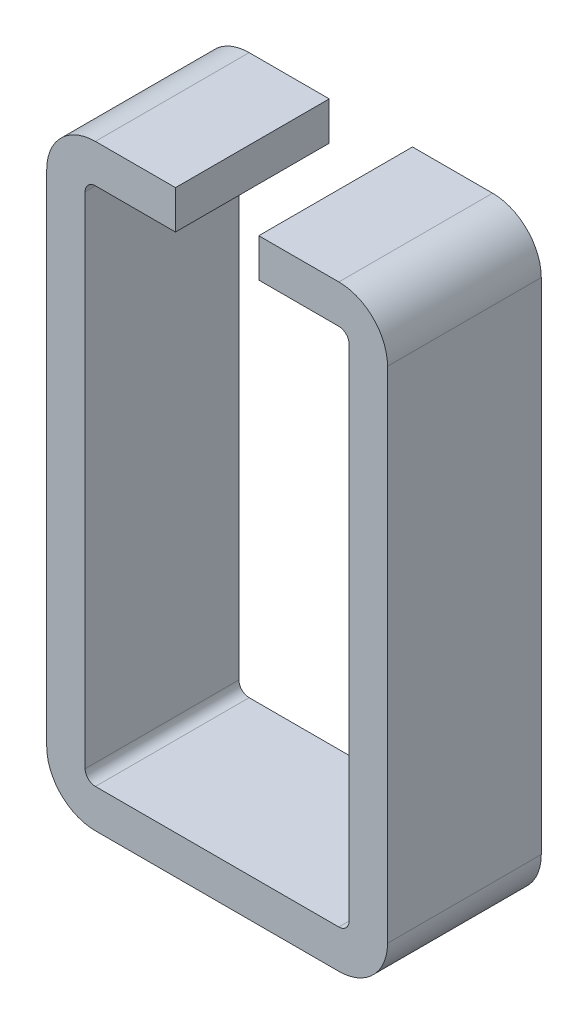
SolidWorks part; units mm, degrees
ref_plane "Front Plane" through (0, 0, 0) normal (0, 0, 1) x (1, 0, 0)
ref_plane "Top Plane" through (0, 0, 0) normal (0, 1, 0) x (1, 0, 0)
ref_plane "Right Plane" through (0, 0, 0) normal (1, 0, 0) x (0, 0, -1)
sketch "Sketch1" plane through (0, 0, 0) normal (0, 0, 1) x (1, 0, 0)
  line L0 (-3.25, 20.3) -> (-3.25, 23.3)
  line L1 (-3.05, 20.9) -> (-3.05, 23.3537) construction
  line L2 (3.25, 23.3) -> (3.25, 20.3)
  line L3 (3.05, 20.9) -> (3.05, 23.3537) construction
  line L94 (-10, -14.58) -> (-10, -19.5)
  line L95 (-9.5, -20) -> (-4.58, -20)
  line L96 (-4.58, -20) -> (-3.125, -18.545)
  line L97 (-3.125, -18.545) -> (-3.125, -18.2)
  line L98 (-3.125, -18.2) -> (-5.5, -18.2)
  line L99 (-5.5, -18.2) -> (-5.5, -16.5607)
  line L100 (-5.5, -16.5607) -> (-2.8393, -13.9)
  line L101 (-2.8393, -13.9) -> (-0.2, -13.9)
  line L102 (-0.2, -13.9) -> (0, -13.7)
  line L103 (0, -13.7) -> (0.2, -13.9)
  line L104 (0.2, -13.9) -> (2.8393, -13.9)
  line L105 (2.8393, -13.9) -> (5.5, -16.5607)
  line L106 (5.5, -16.5607) -> (5.5, -18.2)
  line L107 (5.5, -18.2) -> (3.125, -18.2)
  line L108 (3.125, -18.2) -> (3.125, -18.545)
  line L109 (3.125, -18.545) -> (4.58, -20)
  line L110 (4.58, -20) -> (9.5, -20)
  line L111 (10, -19.5) -> (10, -14.58)
  line L112 (10, -14.58) -> (8.545, -13.125)
  line L113 (8.545, -13.125) -> (8.2, -13.125)
  line L114 (8.2, -13.125) -> (8.2, -15.5)
  line L115 (8.2, -15.5) -> (6.5607, -15.5)
  line L116 (6.5607, -15.5) -> (3.9, -12.8393)
  line L117 (3.9, -12.8393) -> (3.9, -10.2)
  line L118 (3.9, -10.2) -> (3.7, -10)
  line L119 (3.7, -10) -> (3.9, -9.8)
  line L120 (3.9, -9.8) -> (3.9, -7.1607)
  line L121 (3.9, -7.1607) -> (6.5607, -4.5)
  line L122 (6.5607, -4.5) -> (8.2, -4.5)
  line L123 (8.2, -4.5) -> (8.2, -6.875)
  line L124 (8.2, -6.875) -> (8.545, -6.875)
  line L125 (8.545, -6.875) -> (10, -5.42)
  line L126 (10, -5.42) -> (10, 5.42)
  line L127 (10, 5.42) -> (8.545, 6.875)
  line L128 (8.545, 6.875) -> (8.2, 6.875)
  line L129 (8.2, 6.875) -> (8.2, 4.5)
  line L130 (8.2, 4.5) -> (6.5607, 4.5)
  line L131 (6.5607, 4.5) -> (3.9, 7.1607)
  line L132 (3.9, 7.1607) -> (3.9, 9.8)
  line L133 (3.9, 9.8) -> (3.7, 10)
  line L134 (3.7, 10) -> (3.9, 10.2)
  line L135 (3.9, 10.2) -> (3.9, 12.8393)
  line L136 (3.9, 12.8393) -> (6.5607, 15.5)
  line L137 (6.5607, 15.5) -> (8.2, 15.5)
  line L138 (8.2, 15.5) -> (8.2, 13.125)
  line L139 (8.2, 13.125) -> (8.545, 13.125)
  line L140 (8.545, 13.125) -> (10, 14.58)
  line L141 (10, 14.58) -> (10, 19.5)
  line L142 (9.5, 20) -> (4.58, 20)
  line L143 (4.58, 20) -> (3.125, 18.545)
  line L144 (3.125, 18.545) -> (3.125, 18.2)
  line L145 (3.125, 18.2) -> (5.5, 18.2)
  line L146 (5.5, 18.2) -> (5.5, 16.5607)
  line L147 (5.5, 16.5607) -> (2.8393, 13.9)
  line L148 (2.8393, 13.9) -> (0.2, 13.9)
  line L149 (0.2, 13.9) -> (0, 13.7)
  line L150 (0, 13.7) -> (-0.2, 13.9)
  line L151 (-0.2, 13.9) -> (-2.8393, 13.9)
  line L152 (-2.8393, 13.9) -> (-5.5, 16.5607)
  line L153 (-5.5, 16.5607) -> (-5.5, 18.2)
  line L154 (-5.5, 18.2) -> (-3.125, 18.2)
  line L155 (-3.125, 18.2) -> (-3.125, 18.545)
  line L156 (-3.125, 18.545) -> (-4.58, 20)
  line L157 (-4.58, 20) -> (-9.5, 20)
  line L158 (-10, 19.5) -> (-10, 14.58)
  line L159 (-10, 14.58) -> (-8.545, 13.125)
  line L160 (-8.545, 13.125) -> (-8.2, 13.125)
  line L161 (-8.2, 13.125) -> (-8.2, 15.5)
  line L162 (-8.2, 15.5) -> (-6.5607, 15.5)
  line L163 (-6.5607, 15.5) -> (-3.9, 12.8393)
  line L164 (-3.9, 12.8393) -> (-3.9, 10.2)
  line L165 (-3.9, 10.2) -> (-3.7, 10)
  line L166 (-3.7, 10) -> (-3.9, 9.8)
  line L167 (-3.9, 9.8) -> (-3.9, 7.1607)
  line L168 (-3.9, 7.1607) -> (-6.5607, 4.5)
  line L169 (-6.5607, 4.5) -> (-8.2, 4.5)
  line L170 (-8.2, 4.5) -> (-8.2, 6.875)
  line L171 (-8.2, 6.875) -> (-8.545, 6.875)
  line L172 (-8.545, 6.875) -> (-10, 5.42)
  line L173 (-10, 5.42) -> (-10, -5.42)
  line L174 (-10, -5.42) -> (-8.545, -6.875)
  line L175 (-8.545, -6.875) -> (-8.2, -6.875)
  line L176 (-8.2, -6.875) -> (-8.2, -4.5)
  line L177 (-8.2, -4.5) -> (-6.5607, -4.5)
  line L178 (-6.5607, -4.5) -> (-3.9, -7.1607)
  line L179 (-3.9, -7.1607) -> (-3.9, -9.8)
  line L180 (-3.9, -9.8) -> (-3.7, -10)
  line L181 (-3.7, -10) -> (-3.9, -10.2)
  line L182 (-3.9, -10.2) -> (-3.9, -12.8393)
  line L183 (-3.9, -12.8393) -> (-6.5607, -15.5)
  line L184 (-6.5607, -15.5) -> (-8.2, -15.5)
  line L185 (-8.2, -15.5) -> (-8.2, -13.125)
  line L186 (-8.2, -13.125) -> (-8.545, -13.125)
  line L187 (-8.545, -13.125) -> (-10, -14.58)
  line L188 (-10, -14.58) -> (-10, -19.5) construction
  line L189 (-9.5, -20) -> (-4.58, -20) construction
  line L190 (-4.58, -20) -> (-3.125, -18.545) construction
  line L191 (-3.125, -18.545) -> (-3.125, -18.2) construction
  line L192 (-3.125, -18.2) -> (-5.5, -18.2) construction
  line L193 (-5.5, -18.2) -> (-5.5, -16.5607) construction
  line L194 (-5.5, -16.5607) -> (-2.8393, -13.9) construction
  line L195 (-2.8393, -13.9) -> (-0.2, -13.9) construction
  line L196 (-0.2, -13.9) -> (0, -13.7) construction
  line L197 (0, -13.7) -> (0.2, -13.9) construction
  line L198 (0.2, -13.9) -> (2.8393, -13.9) construction
  line L199 (2.8393, -13.9) -> (5.5, -16.5607) construction
  line L200 (5.5, -16.5607) -> (5.5, -18.2) construction
  line L201 (5.5, -18.2) -> (3.125, -18.2) construction
  line L202 (3.125, -18.2) -> (3.125, -18.545) construction
  line L203 (3.125, -18.545) -> (4.58, -20) construction
  line L204 (4.58, -20) -> (9.5, -20) construction
  line L205 (10, -19.5) -> (10, -14.58) construction
  line L206 (10, -14.58) -> (8.545, -13.125) construction
  line L207 (8.545, -13.125) -> (8.2, -13.125) construction
  line L208 (8.2, -13.125) -> (8.2, -15.5) construction
  line L209 (8.2, -15.5) -> (6.5607, -15.5) construction
  line L210 (6.5607, -15.5) -> (3.9, -12.8393) construction
  line L211 (3.9, -12.8393) -> (3.9, -10.2) construction
  line L212 (3.9, -10.2) -> (3.7, -10) construction
  line L213 (3.7, -10) -> (3.9, -9.8) construction
  line L214 (3.9, -9.8) -> (3.9, -7.1607) construction
  line L215 (3.9, -7.1607) -> (6.5607, -4.5) construction
  line L216 (6.5607, -4.5) -> (8.2, -4.5) construction
  line L217 (8.2, -4.5) -> (8.2, -6.875) construction
  line L218 (8.2, -6.875) -> (8.545, -6.875) construction
  line L219 (8.545, -6.875) -> (10, -5.42) construction
  line L220 (10, -5.42) -> (10, 5.42) construction
  line L221 (10, 5.42) -> (8.545, 6.875) construction
  line L222 (8.545, 6.875) -> (8.2, 6.875) construction
  line L223 (8.2, 6.875) -> (8.2, 4.5) construction
  line L224 (8.2, 4.5) -> (6.5607, 4.5) construction
  line L225 (6.5607, 4.5) -> (3.9, 7.1607) construction
  line L226 (3.9, 7.1607) -> (3.9, 9.8) construction
  line L227 (3.9, 9.8) -> (3.7, 10) construction
  line L228 (3.7, 10) -> (3.9, 10.2) construction
  line L229 (3.9, 10.2) -> (3.9, 12.8393) construction
  line L230 (3.9, 12.8393) -> (6.5607, 15.5) construction
  line L231 (6.5607, 15.5) -> (8.2, 15.5) construction
  line L232 (8.2, 15.5) -> (8.2, 13.125) construction
  line L233 (8.2, 13.125) -> (8.545, 13.125) construction
  line L234 (8.545, 13.125) -> (10, 14.58) construction
  line L235 (10, 14.58) -> (10, 19.5) construction
  line L236 (9.5, 20) -> (4.58, 20) construction
  line L237 (4.58, 20) -> (3.125, 18.545) construction
  line L238 (3.125, 18.545) -> (3.125, 18.2) construction
  line L239 (3.125, 18.2) -> (5.5, 18.2) construction
  line L240 (5.5, 18.2) -> (5.5, 16.5607) construction
  line L241 (5.5, 16.5607) -> (2.8393, 13.9) construction
  line L242 (2.8393, 13.9) -> (0.2, 13.9) construction
  line L243 (0.2, 13.9) -> (0, 13.7) construction
  line L244 (0, 13.7) -> (-0.2, 13.9) construction
  line L245 (-0.2, 13.9) -> (-2.8393, 13.9) construction
  line L246 (-2.8393, 13.9) -> (-5.5, 16.5607) construction
  line L247 (-5.5, 16.5607) -> (-5.5, 18.2) construction
  line L248 (-5.5, 18.2) -> (-3.125, 18.2) construction
  line L249 (-3.125, 18.2) -> (-3.125, 18.545) construction
  line L250 (-3.125, 18.545) -> (-4.58, 20) construction
  line L251 (-4.58, 20) -> (-9.5, 20) construction
  line L252 (-10, 19.5) -> (-10, 14.58) construction
  line L253 (-10, 14.58) -> (-8.545, 13.125) construction
  line L254 (-8.545, 13.125) -> (-8.2, 13.125) construction
  line L255 (-8.2, 13.125) -> (-8.2, 15.5) construction
  line L256 (-8.2, 15.5) -> (-6.5607, 15.5) construction
  line L257 (-6.5607, 15.5) -> (-3.9, 12.8393) construction
  line L258 (-3.9, 12.8393) -> (-3.9, 10.2) construction
  line L259 (-3.9, 10.2) -> (-3.7, 10) construction
  line L260 (-3.7, 10) -> (-3.9, 9.8) construction
  line L261 (-3.9, 9.8) -> (-3.9, 7.1607) construction
  line L262 (-3.9, 7.1607) -> (-6.5607, 4.5) construction
  line L263 (-6.5607, 4.5) -> (-8.2, 4.5) construction
  line L264 (-8.2, 4.5) -> (-8.2, 6.875) construction
  line L265 (-8.2, 6.875) -> (-8.545, 6.875) construction
  line L266 (-8.545, 6.875) -> (-10, 5.42) construction
  line L267 (-10, 5.42) -> (-10, -5.42) construction
  line L268 (-10, -5.42) -> (-8.545, -6.875) construction
  line L269 (-8.545, -6.875) -> (-8.2, -6.875) construction
  line L270 (-8.2, -6.875) -> (-8.2, -4.5) construction
  line L271 (-8.2, -4.5) -> (-6.5607, -4.5) construction
  line L272 (-6.5607, -4.5) -> (-3.9, -7.1607) construction
  line L273 (-3.9, -7.1607) -> (-3.9, -9.8) construction
  line L274 (-3.9, -9.8) -> (-3.7, -10) construction
  line L275 (-3.7, -10) -> (-3.9, -10.2) construction
  line L276 (-3.9, -10.2) -> (-3.9, -12.8393) construction
  line L277 (-3.9, -12.8393) -> (-6.5607, -15.5) construction
  line L278 (-6.5607, -15.5) -> (-8.2, -15.5) construction
  line L279 (-8.2, -15.5) -> (-8.2, -13.125) construction
  line L280 (-8.2, -13.125) -> (-8.545, -13.125) construction
  line L281 (-8.545, -13.125) -> (-10, -14.58) construction
  line L282 (-10.3, 14.4557) -> (-10.3, 5.5443)
  line L283 (10.3, 14.4557) -> (10.3, 5.5443)
  line L284 (10.3, -5.5443) -> (10.3, -14.4557)
  line L285 (-10.3, -5.5443) -> (-10.3, -14.4557)
  line L286 (-4.4557, -20.3) -> (4.4557, -20.3)
  line L287 (-4.4557, 20.3) -> (4.4557, 20.3)
  line L288 (-4.4557, 23.3) -> (-9.5, 23.3)
  line L289 (-13.3, 19.5) -> (-13.3, 14.4557)
  line L290 (-13.3, 14.4557) -> (-13.3, 5.5443)
  line L291 (-13.3, 5.5443) -> (-13.3, -5.5443)
  line L292 (-13.3, -5.5443) -> (-13.3, -14.4557)
  line L293 (-13.3, -14.4557) -> (-13.3, -19.5)
  line L294 (-9.5, -23.3) -> (-4.4557, -23.3)
  line L295 (-4.4557, -23.3) -> (4.4557, -23.3)
  line L296 (4.4557, -23.3) -> (9.5, -23.3)
  line L297 (13.3, -19.5) -> (13.3, -14.4557)
  line L298 (13.3, -5.5443) -> (13.3, -14.4557)
  line L299 (13.3, -5.5443) -> (13.3, 5.5443)
  line L300 (13.3, 14.4557) -> (13.3, 5.5443)
  line L301 (13.3, 14.4557) -> (13.3, 19.5)
  line L302 (9.5, 23.3) -> (4.4557, 23.3)
  line L303 (-4.4557, 23.3) -> (4.4557, 23.3)
  line L376 (-10.3, -14.4557) -> (-10.3, -19.5)
  line L377 (-9.5, -20.3) -> (-4.4557, -20.3)
  line L378 (-4.4557, -20.3) -> (-2.825, -18.6693)
  line L379 (-2.825, -18.6693) -> (-2.825, -17.9)
  line L380 (-2.825, -17.9) -> (-5.2, -17.9)
  line L381 (-5.2, -17.9) -> (-5.2, -16.6849)
  line L382 (-5.2, -16.6849) -> (-2.7151, -14.2)
  line L383 (-2.7151, -14.2) -> (-0.0757, -14.2)
  line L384 (2.7151, -14.2) -> (5.2, -16.6849)
  line L385 (5.2, -16.6849) -> (5.2, -17.9)
  line L386 (5.2, -17.9) -> (2.825, -17.9)
  line L387 (2.825, -17.9) -> (2.825, -18.6693)
  line L388 (2.825, -18.6693) -> (4.4557, -20.3)
  line L389 (4.4557, -20.3) -> (9.5, -20.3)
  line L390 (10.3, -19.5) -> (10.3, -14.4557)
  line L391 (10.3, -14.4557) -> (8.6693, -12.825)
  line L392 (8.6693, -12.825) -> (7.9, -12.825)
  line L393 (7.9, -12.825) -> (7.9, -15.2)
  line L394 (7.9, -15.2) -> (6.6849, -15.2)
  line L395 (6.6849, -15.2) -> (4.2, -12.7151)
  line L396 (4.2, -12.7151) -> (4.2, -10.0757)
  line L397 (4.2, -7.2849) -> (6.6849, -4.8)
  line L398 (6.6849, -4.8) -> (7.9, -4.8)
  line L399 (7.9, -4.8) -> (7.9, -7.175)
  line L400 (7.9, -7.175) -> (8.6693, -7.175)
  line L401 (8.6693, -7.175) -> (10.3, -5.5443)
  line L402 (10.3, -5.5443) -> (10.3, 5.5443)
  line L403 (10.3, 5.5443) -> (8.6693, 7.175)
  line L404 (8.6693, 7.175) -> (7.9, 7.175)
  line L405 (7.9, 7.175) -> (7.9, 4.8)
  line L406 (7.9, 4.8) -> (6.6849, 4.8)
  line L407 (6.6849, 4.8) -> (4.2, 7.2849)
  line L408 (4.2, 7.2849) -> (4.2, 9.9243)
  line L409 (4.2, 12.7151) -> (6.6849, 15.2)
  line L410 (6.6849, 15.2) -> (7.9, 15.2)
  line L411 (7.9, 15.2) -> (7.9, 12.825)
  line L412 (7.9, 12.825) -> (8.6693, 12.825)
  line L413 (8.6693, 12.825) -> (10.3, 14.4557)
  line L414 (10.3, 14.4557) -> (10.3, 19.5)
  line L415 (9.5, 20.3) -> (4.4557, 20.3)
  line L416 (4.4557, 20.3) -> (2.825, 18.6693)
  line L417 (2.825, 18.6693) -> (2.825, 17.9)
  line L418 (2.825, 17.9) -> (5.2, 17.9)
  line L419 (5.2, 17.9) -> (5.2, 16.6849)
  line L420 (5.2, 16.6849) -> (2.7151, 14.2)
  line L421 (2.7151, 14.2) -> (0.0757, 14.2)
  line L422 (-2.7151, 14.2) -> (-5.2, 16.6849)
  line L423 (-5.2, 16.6849) -> (-5.2, 17.9)
  line L424 (-5.2, 17.9) -> (-2.825, 17.9)
  line L425 (-2.825, 17.9) -> (-2.825, 18.6693)
  line L426 (-2.825, 18.6693) -> (-4.4557, 20.3)
  line L427 (-4.4557, 20.3) -> (-9.5, 20.3)
  line L428 (-10.3, 19.5) -> (-10.3, 14.4557)
  line L429 (-10.3, 14.4557) -> (-8.6693, 12.825)
  line L430 (-8.6693, 12.825) -> (-7.9, 12.825)
  line L431 (-7.9, 12.825) -> (-7.9, 15.2)
  line L432 (-7.9, 15.2) -> (-6.6849, 15.2)
  line L433 (-6.6849, 15.2) -> (-4.2, 12.7151)
  line L434 (-4.2, 12.7151) -> (-4.2, 10.0757)
  line L435 (-4.2, 7.2849) -> (-6.6849, 4.8)
  line L436 (-6.6849, 4.8) -> (-7.9, 4.8)
  line L437 (-7.9, 4.8) -> (-7.9, 7.175)
  line L438 (-7.9, 7.175) -> (-8.6693, 7.175)
  line L439 (-8.6693, 7.175) -> (-10.3, 5.5443)
  line L440 (-10.3, 5.5443) -> (-10.3, -5.5443)
  line L441 (-10.3, -5.5443) -> (-8.6693, -7.175)
  line L442 (-8.6693, -7.175) -> (-7.9, -7.175)
  line L443 (-7.9, -7.175) -> (-7.9, -4.8)
  line L444 (-7.9, -4.8) -> (-6.6849, -4.8)
  line L445 (-6.6849, -4.8) -> (-4.2, -7.2849)
  line L446 (-4.2, -7.2849) -> (-4.2, -9.9243)
  line L447 (-4.2, -12.7151) -> (-6.6849, -15.2)
  line L448 (-6.6849, -15.2) -> (-7.9, -15.2)
  line L449 (-7.9, -15.2) -> (-7.9, -12.825)
  line L450 (-7.9, -12.825) -> (-8.6693, -12.825)
  line L451 (-8.6693, -12.825) -> (-10.3, -14.4557)
  line L452 (-10.3, -14.4557) -> (-10.3, -19.5)
  line L453 (-9.5, -20.3) -> (-4.4557, -20.3)
  line L454 (-4.4557, -20.3) -> (-2.825, -18.6693)
  line L455 (-2.825, -18.6693) -> (-2.825, -17.9)
  line L456 (-2.825, -17.9) -> (-5.2, -17.9)
  line L457 (-5.2, -17.9) -> (-5.2, -16.6849)
  line L458 (-5.2, -16.6849) -> (-2.7151, -14.2)
  line L459 (-2.7151, -14.2) -> (-0.0757, -14.2)
  line L460 (2.7151, -14.2) -> (5.2, -16.6849)
  line L461 (5.2, -16.6849) -> (5.2, -17.9)
  line L462 (5.2, -17.9) -> (2.825, -17.9)
  line L463 (2.825, -17.9) -> (2.825, -18.6693)
  line L464 (2.825, -18.6693) -> (4.4557, -20.3)
  line L465 (4.4557, -20.3) -> (9.5, -20.3)
  line L466 (10.3, -19.5) -> (10.3, -14.4557)
  line L467 (10.3, -14.4557) -> (8.6693, -12.825)
  line L468 (8.6693, -12.825) -> (7.9, -12.825)
  line L469 (7.9, -12.825) -> (7.9, -15.2)
  line L470 (7.9, -15.2) -> (6.6849, -15.2)
  line L471 (6.6849, -15.2) -> (4.2, -12.7151)
  line L472 (4.2, -12.7151) -> (4.2, -10.0757)
  line L473 (4.2, -7.2849) -> (6.6849, -4.8)
  line L474 (6.6849, -4.8) -> (7.9, -4.8)
  line L475 (7.9, -4.8) -> (7.9, -7.175)
  line L476 (7.9, -7.175) -> (8.6693, -7.175)
  line L477 (8.6693, -7.175) -> (10.3, -5.5443)
  line L478 (10.3, -5.5443) -> (10.3, 5.5443)
  line L479 (10.3, 5.5443) -> (8.6693, 7.175)
  line L480 (8.6693, 7.175) -> (7.9, 7.175)
  line L481 (7.9, 7.175) -> (7.9, 4.8)
  line L482 (7.9, 4.8) -> (6.6849, 4.8)
  line L483 (6.6849, 4.8) -> (4.2, 7.2849)
  line L484 (4.2, 7.2849) -> (4.2, 9.9243)
  line L485 (4.2, 12.7151) -> (6.6849, 15.2)
  line L486 (6.6849, 15.2) -> (7.9, 15.2)
  line L487 (7.9, 15.2) -> (7.9, 12.825)
  line L488 (7.9, 12.825) -> (8.6693, 12.825)
  line L489 (8.6693, 12.825) -> (10.3, 14.4557)
  line L490 (10.3, 14.4557) -> (10.3, 19.5)
  line L491 (9.5, 20.3) -> (4.4557, 20.3)
  line L492 (4.4557, 20.3) -> (2.825, 18.6693)
  line L493 (2.825, 18.6693) -> (2.825, 17.9)
  line L494 (2.825, 17.9) -> (5.2, 17.9)
  line L495 (5.2, 17.9) -> (5.2, 16.6849)
  line L496 (5.2, 16.6849) -> (2.7151, 14.2)
  line L497 (2.7151, 14.2) -> (0.0757, 14.2)
  line L498 (-2.7151, 14.2) -> (-5.2, 16.6849)
  line L499 (-5.2, 16.6849) -> (-5.2, 17.9)
  line L500 (-5.2, 17.9) -> (-2.825, 17.9)
  line L501 (-2.825, 17.9) -> (-2.825, 18.6693)
  line L502 (-2.825, 18.6693) -> (-4.4557, 20.3)
  line L503 (-4.4557, 20.3) -> (-9.5, 20.3)
  line L504 (-10.3, 19.5) -> (-10.3, 14.4557)
  line L505 (-10.3, 14.4557) -> (-8.6693, 12.825)
  line L506 (-8.6693, 12.825) -> (-7.9, 12.825)
  line L507 (-7.9, 12.825) -> (-7.9, 15.2)
  line L508 (-7.9, 15.2) -> (-6.6849, 15.2)
  line L509 (-6.6849, 15.2) -> (-4.2, 12.7151)
  line L510 (-4.2, 12.7151) -> (-4.2, 10.0757)
  line L511 (-4.2, 7.2849) -> (-6.6849, 4.8)
  line L512 (-6.6849, 4.8) -> (-7.9, 4.8)
  line L513 (-7.9, 4.8) -> (-7.9, 7.175)
  line L514 (-7.9, 7.175) -> (-8.6693, 7.175)
  line L515 (-8.6693, 7.175) -> (-10.3, 5.5443)
  line L516 (-10.3, 5.5443) -> (-10.3, -5.5443)
  line L517 (-10.3, -5.5443) -> (-8.6693, -7.175)
  line L518 (-8.6693, -7.175) -> (-7.9, -7.175)
  line L519 (-7.9, -7.175) -> (-7.9, -4.8)
  line L520 (-7.9, -4.8) -> (-6.6849, -4.8)
  line L521 (-6.6849, -4.8) -> (-4.2, -7.2849)
  line L522 (-4.2, -7.2849) -> (-4.2, -9.9243)
  line L523 (-4.2, -12.7151) -> (-6.6849, -15.2)
  line L524 (-6.6849, -15.2) -> (-7.9, -15.2)
  line L525 (-7.9, -15.2) -> (-7.9, -12.825)
  line L526 (-7.9, -12.825) -> (-8.6693, -12.825)
  line L527 (-8.6693, -12.825) -> (-10.3, -14.4557)
  line L528 (-0.0757, -14.2) -> (0, -14.1243)
  line L529 (-0.0757, -14.2) -> (0, -14.1243)
  line L530 (0, -14.1243) -> (0.0757, -14.2)
  line L531 (0, -14.1243) -> (0.0757, -14.2)
  line L532 (0.0757, -14.2) -> (2.7151, -14.2)
  line L533 (0.0757, -14.2) -> (2.7151, -14.2)
  line L534 (4.2, -10.0757) -> (4.1243, -10)
  line L535 (4.2, -10.0757) -> (4.1243, -10)
  line L536 (4.1243, -10) -> (4.2, -9.9243)
  line L537 (4.1243, -10) -> (4.2, -9.9243)
  line L538 (4.2, -9.9243) -> (4.2, -7.2849)
  line L539 (4.2, -9.9243) -> (4.2, -7.2849)
  line L540 (4.2, 9.9243) -> (4.1243, 10)
  line L541 (4.2, 9.9243) -> (4.1243, 10)
  line L542 (4.1243, 10) -> (4.2, 10.0757)
  line L543 (4.1243, 10) -> (4.2, 10.0757)
  line L544 (4.2, 10.0757) -> (4.2, 12.7151)
  line L545 (4.2, 10.0757) -> (4.2, 12.7151)
  line L546 (0.0757, 14.2) -> (0, 14.1243)
  line L547 (0.0757, 14.2) -> (0, 14.1243)
  line L548 (0, 14.1243) -> (-0.0757, 14.2)
  line L549 (0, 14.1243) -> (-0.0757, 14.2)
  line L550 (-0.0757, 14.2) -> (-2.7151, 14.2)
  line L551 (-0.0757, 14.2) -> (-2.7151, 14.2)
  line L552 (-4.2, 10.0757) -> (-4.1243, 10)
  line L553 (-4.2, 10.0757) -> (-4.1243, 10)
  line L554 (-4.1243, 10) -> (-4.2, 9.9243)
  line L555 (-4.1243, 10) -> (-4.2, 9.9243)
  line L556 (-4.2, 9.9243) -> (-4.2, 7.2849)
  line L557 (-4.2, 9.9243) -> (-4.2, 7.2849)
  line L558 (-4.2, -9.9243) -> (-4.1243, -10)
  line L559 (-4.2, -9.9243) -> (-4.1243, -10)
  line L560 (-4.1243, -10) -> (-4.2, -10.0757)
  line L561 (-4.1243, -10) -> (-4.2, -10.0757)
  line L562 (-4.2, -10.0757) -> (-4.2, -12.7151)
  line L563 (-4.2, -10.0757) -> (-4.2, -12.7151)
  arc A4 (-10, -19.5) -> (-9.5, -20) centre (-9.5, -19.5) ccw
  arc A5 (9.5, -20) -> (10, -19.5) centre (9.5, -19.5) ccw
  arc A6 (10, 19.5) -> (9.5, 20) centre (9.5, 19.5) ccw
  arc A7 (-9.5, 20) -> (-10, 19.5) centre (-9.5, 19.5) ccw
  arc A8 (-10, -19.5) -> (-9.5, -20) centre (-9.5, -19.5) ccw construction
  arc A9 (9.5, -20) -> (10, -19.5) centre (9.5, -19.5) ccw construction
  arc A10 (10, 19.5) -> (9.5, 20) centre (9.5, 19.5) ccw construction
  arc A11 (-9.5, 20) -> (-10, 19.5) centre (-9.5, 19.5) ccw construction
  arc A12 (-9.5, 23.3) -> (-13.3, 19.5) centre (-9.5, 19.5) ccw
  arc A13 (-13.3, -19.5) -> (-9.5, -23.3) centre (-9.5, -19.5) ccw
  arc A14 (9.5, -23.3) -> (13.3, -19.5) centre (9.5, -19.5) ccw
  arc A15 (13.3, 19.5) -> (9.5, 23.3) centre (9.5, 19.5) ccw
  arc A16 (-10.3, -19.5) -> (-9.5, -20.3) centre (-9.5, -19.5) ccw
  arc A17 (9.5, -20.3) -> (10.3, -19.5) centre (9.5, -19.5) ccw
  arc A18 (10.3, 19.5) -> (9.5, 20.3) centre (9.5, 19.5) ccw
  arc A19 (-9.5, 20.3) -> (-10.3, 19.5) centre (-9.5, 19.5) ccw
  arc A20 (-10.3, -19.5) -> (-9.5, -20.3) centre (-9.5, -19.5) ccw
  arc A21 (9.5, -20.3) -> (10.3, -19.5) centre (9.5, -19.5) ccw
  arc A22 (10.3, 19.5) -> (9.5, 20.3) centre (9.5, 19.5) ccw
  arc A23 (-9.5, 20.3) -> (-10.3, 19.5) centre (-9.5, 19.5) ccw
  dimension "D4" = 0.2
  dimension "D5" = 0.2
  dimension "D1" = 0
  dimension "D2" = 0.3
  dimension "D3" = 3
extrude "Boss-Extrude1" add sketch "Sketch1" against normal blind 12 contours L301 A15 L302 L303 L288 A12 L289 L290 L291 L292 L293 A13 L294 L295 L296 A14 L297 L298 L299 L300 A23 L503 L287 L491 A22 L490 L283 L478 L284 L466 A21 L465 L286 L453 A20 L452 L285 L516 L282 L504
